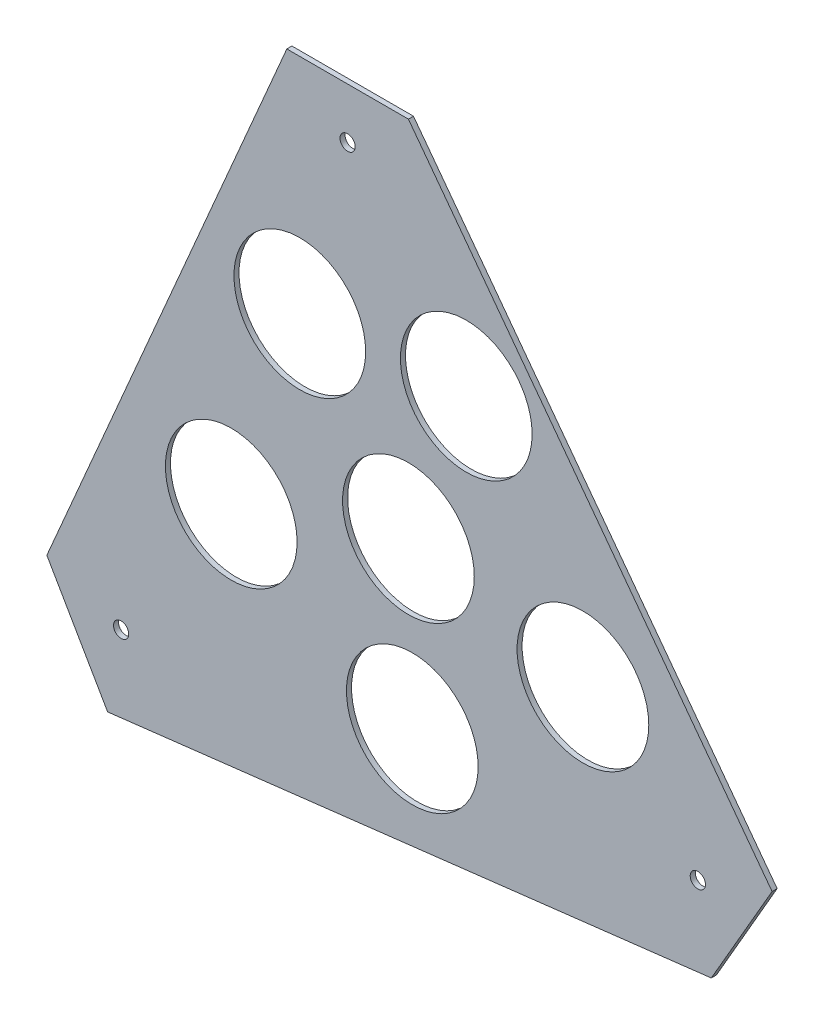
SolidWorks part; units mm, degrees
material "0.6010 (EN-GJL-100)"
ref_plane "Alzado" through (0, 0, 0) normal (0, 0, 1) x (1, 0, 0)
ref_plane "Planta" through (0, 0, 0) normal (0, 1, 0) x (1, 0, 0)
ref_plane "Vista lateral" through (0, 0, 0) normal (1, 0, 0) x (0, 0, -1)
sketch "Croquis1" plane through (0, 0, 0) normal (0, 0, 1) x (1, 0, 0)
  line L0 (75.6538, -20.425) -> (63.6538, -41.2096)
  line L1 (-20.1383, 75.7306) -> (-67.5155, -34.521)
  line L2 (-55.5155, -55.3056) -> (63.6538, -41.2096)
  line L3 (75.6538, -20.425) -> (3.8617, 75.7306)
  line L4 (-55.5155, -55.3056) -> (-67.5155, -34.521)
  line L5 (-20.1383, 75.7306) -> (3.8617, 75.7306)
  circle A0 centre (0, 0) radius 48.4015 construction
  circle A1 centre (-8.1383, 65.7306) radius 1.5
  circle A2 centre (60.9935, -25.8173) radius 1.5
  circle A3 centre (-52.8552, -39.9133) radius 1.5
  circle A4 centre (-17.5803, 31.7435) radius 13
  circle A5 centre (15.2805, 34.0733) radius 13
  circle A7 centre (38.3089, -4.1304) radius 13
  circle A8 centre (3.8617, 4.0115) radius 13
  circle A9 centre (4.6288, -28.111) radius 13
  circle A10 centre (-31.1123, -7.5785) radius 13
  point P14 (0, 0)
  point P15 (0, 12.59)
  point P19 (0, 0)
  point P22 (0, 0)
  point P23 (-8.1383, 75.7306)
  point P28 (-17.5803, 31.7435)
  point P29 (15.2805, 34.0733)
  point P30 (3.8617, 4.0115)
  point P31 (38.3089, -4.1304)
  dimension "D2" = 3
  dimension "D6" = 26
  dimension "D1" = 24
  dimension "D3" = 3
  dimension "D4" = 10
  dimension "D7" = 120
  dimension "D5" = 3
extrude "Saliente-Extruir1" add sketch "Croquis1" along normal blind 1
